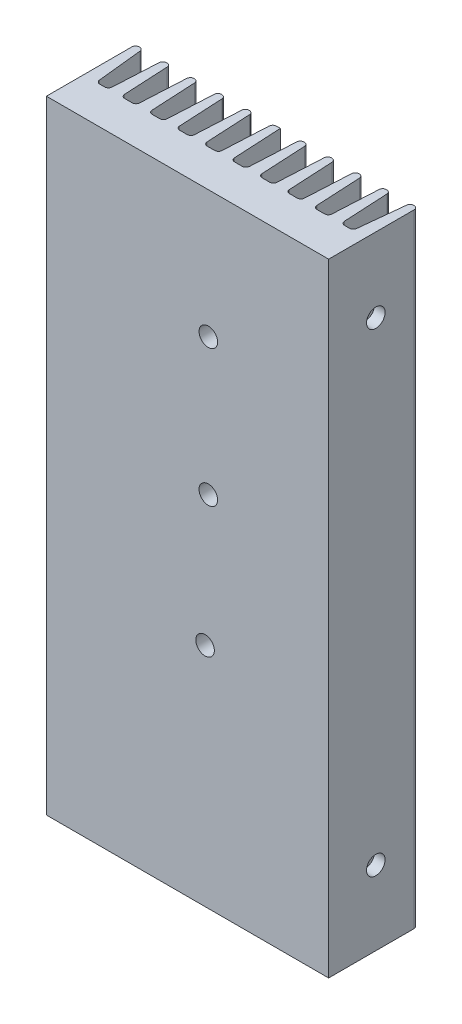
SolidWorks part; units mm, degrees
ref_plane "Front Plane" through (0, 0, 0) normal (0, 0, 1) x (1, 0, 0)
ref_plane "Top Plane" through (0, 0, 0) normal (0, 1, 0) x (1, 0, 0)
ref_plane "Right Plane" through (0, 0, 0) normal (1, 0, 0) x (0, 0, -1)
sketch "Sketch1" plane through (0, 0, 0) normal (0, 1, 0) x (1, 0, 0)
  line L0 (0, 12) -> (0, 0)
  line L1 (0, 0) -> (38, 0)
  line L3 (0, 12) -> (1, 12)
  line L4 (1, 12) -> (1.7357, 5)
  line L26 (1.7357, 5) -> (36.2643, 5)
  line L32 (37, 12) -> (38, 12)
  line L41 (38, 0) -> (38, 12)
  line L42 (36.2643, 5) -> (37, 12)
  dimension "D1" = 38
  dimension "D2" = 12
  dimension "D3" = 6
  dimension "D7" = 6
  dimension "D21" = 1
extrude "Extrude1" add sketch "Sketch1" along normal blind 83.82
sketch "Sketch3" plane through (0, 83.82, 0) normal (0, 1, 0) x (1, 0, 0)
  line L0 (3.3331, 5) -> (3.7, 12)
  line L1 (3.7, 12) -> (4.7, 12)
  line L2 (4.7, 12) -> (5.0669, 5)
  line L3 (3.3331, 5) -> (5.0669, 5)
  line L4 (4.2, 12) -> (4.2, -2.4726) construction
  line L5 (0, 12) -> (0, 0) construction
  dimension "D1" = 4.2
  dimension "D2" = 1
extrude "Boss-Extrude1" add sketch "Sketch3" against normal up to surface (83.82 mm away) up to face at (19, 0, -7.25)
pattern_linear "LPattern1" count 9 spacing 3.7 along (1, 0, 0) of "Boss-Extrude1"
fillet "Fillet1" radius 0.5 20 edges at (36.2643, 41.91, -5) (30.9669, 41.91, -5) (29.2331, 41.91, -5) (27.2669, 41.91, -5) (25.5331, 41.91, -5) (23.5669, 41.91, -5) (21.8331, 41.91, -5) (19.8669, 41.91, -5) (18.1331, 41.91, -5) (16.1669, 41.91, -5) (14.4331, 41.91, -5) (12.4669, 41.91, -5) (10.7331, 41.91, -5) (8.7669, 41.91, -5) (7.0331, 41.91, -5) (1.7357, 41.91, -5) (5.0669, 41.91, -5) (3.3331, 41.91, -5) (34.6669, 41.91, -5) (32.9331, 41.91, -5)
fillet "Fillet2" radius 0.5 21 edges at (38, 41.91, -12) (37, 41.91, -12) (34.3, 41.91, -12) (33.3, 41.91, -12) (30.6, 41.91, -12) (29.6, 41.91, -12) (26.9, 41.91, -12) (25.9, 41.91, -12) (23.2, 41.91, -12) (22.2, 41.91, -12) (18.5, 41.91, -12) (15.8, 41.91, -12) (14.8, 41.91, -12) (12.1, 41.91, -12) (11.1, 41.91, -12) (8.4, 41.91, -12) (7.4, 41.91, -12) (4.7, 41.91, -12) (3.7, 41.91, -12) (1, 41.91, -12) (0, 41.91, -12)
sketch "Sketch5" plane through (38, 0, 0) normal (1, 0, 0) x (0, 0, -1)
  line L0 (0, 83.82) -> (0, 0) construction
  line L1 (5.4477, 83.82) -> (11.5523, 83.82) construction
  line L2 (0, 0) -> (11.5, 0) construction
  circle A0 centre (6.35, 73.82) radius 2.1
  circle A1 centre (6.35, 10) radius 2.1
  point P4 (8.5, 83.82)
  dimension "D1" = 6.35
  dimension "D2" = 10
  dimension "D3" = 4.2
  dimension "D4" = 10
  dimension "D6" = 4.2
  dimension "D5" = 6.35
extrude "Cut-Extrude1" [suppressed] cut sketch "Sketch5" against normal blind 2.5
hole_wizard "M3x0.5 Tapped Hole1" positions "Sketch7" profile "Sketch6" tap size "M3x0.5" standard "Ansi Metric"
sketch "Sketch7" plane through (38, 0, 0) normal (1, 0, 0) x (0, 0, -1)
  line L0 (0, 83.82) -> (0, 0) construction
  line L1 (0, 83.82) -> (11.5, 83.82) construction
  line L2 (0, 0) -> (11.5, 0) construction
  point P0 (6.35, 73.82)
  point P6 (6.35, 10)
  dimension "D1" = 6.35
  dimension "D2" = 10
  dimension "D3" = 6.35
  dimension "D4" = 10
sketch "Sketch6" plane through (38, 73.82, -6.35) normal (0, 1, 0) x (0, 0, -1)
  line L0 (0, 0) -> (0, 7.2511)
  line L1 (0, 7.2511) -> (1.25, 6.5)
  line L2 (1.25, 6.5) -> (1.25, 0)
  line L5 (1.25, 0) -> (0, 0)
  line L10 (0, 7.2511) -> (-1.25, 6.5) construction
  line L11 (0, -6.35) -> (0, 107.95) construction
  dimension "Tap Drill Dia." = 2.5
  dimension "Tap Drill Depth" = 6.5
  dimension "Drill Angle" = 118
cosmetic thread "Hole Thread1" parameters "D1"=5, "D2"=3
cosmetic thread "Hole Thread2" parameters "D1"=5, "D2"=3
hole_wizard "M3x0.5 Tapped Hole2" positions "Sketch9" profile "Sketch8" tap size "M3x0.5" standard "Ansi Metric"
sketch "Sketch9" plane through (0, 0, 0) normal (0, 0, 1) x (1, 0, 0)
  line L0 (0, 83.82) -> (38, 83.82) construction
  line L1 (38, 83.82) -> (38, 0) construction
  point P0 (21.8, 66.67)
  point P1 (21.8, 48.26)
  dimension "D1" = 17.15
  dimension "D2" = 16.2
  dimension "D3" = 16.2
  dimension "D4" = 35.56
sketch "Sketch8" plane through (21.8, 66.67, 0) normal (1, 0, 0) x (0, -1, 0)
  line L0 (0, 0) -> (0, 5.7511)
  line L1 (0, 5.7511) -> (1.25, 5)
  line L2 (1.25, 5) -> (1.25, 0)
  line L5 (1.25, 0) -> (0, 0)
  line L10 (0, 5.7511) -> (-1.25, 5) construction
  line L11 (0, -6.35) -> (0, 107.95) construction
  dimension "Tap Drill Dia." = 2.5
  dimension "Tap Drill Depth" = 5
  dimension "Drill Angle" = 118
cosmetic thread "Hole Thread3" parameters "D1"=5, "D2"=3
cosmetic thread "Hole Thread4" parameters "D1"=5, "D2"=3
hole_wizard "M3x0.5 Tapped Hole3" positions "Sketch11" profile "Sketch10" tap size "M3x0.5" standard "Ansi Metric"
sketch "Sketch11" plane through (0, 0, 0) normal (0, 0, 1) x (1, 0, 0)
  line L0 (38, 83.82) -> (38, 0) construction
  line L1 (0, 83.82) -> (38, 83.82) construction
  point P0 (21.36, 30.48)
  dimension "D1" = 16.64
  dimension "D2" = 53.34
sketch "Sketch10" plane through (21.36, 30.48, 0) normal (1, 0, 0) x (0, -1, 0)
  line L0 (0, 0) -> (0, 5.7511)
  line L1 (0, 5.7511) -> (1.25, 5)
  line L2 (1.25, 5) -> (1.25, 0)
  line L5 (1.25, 0) -> (0, 0)
  line L10 (0, 5.7511) -> (-1.25, 5) construction
  line L11 (0, -6.35) -> (0, 107.95) construction
  dimension "Tap Drill Dia." = 2.5
  dimension "Tap Drill Depth" = 5
  dimension "Drill Angle" = 118
cosmetic thread "Hole Thread5" parameters "D1"=5, "D2"=3
